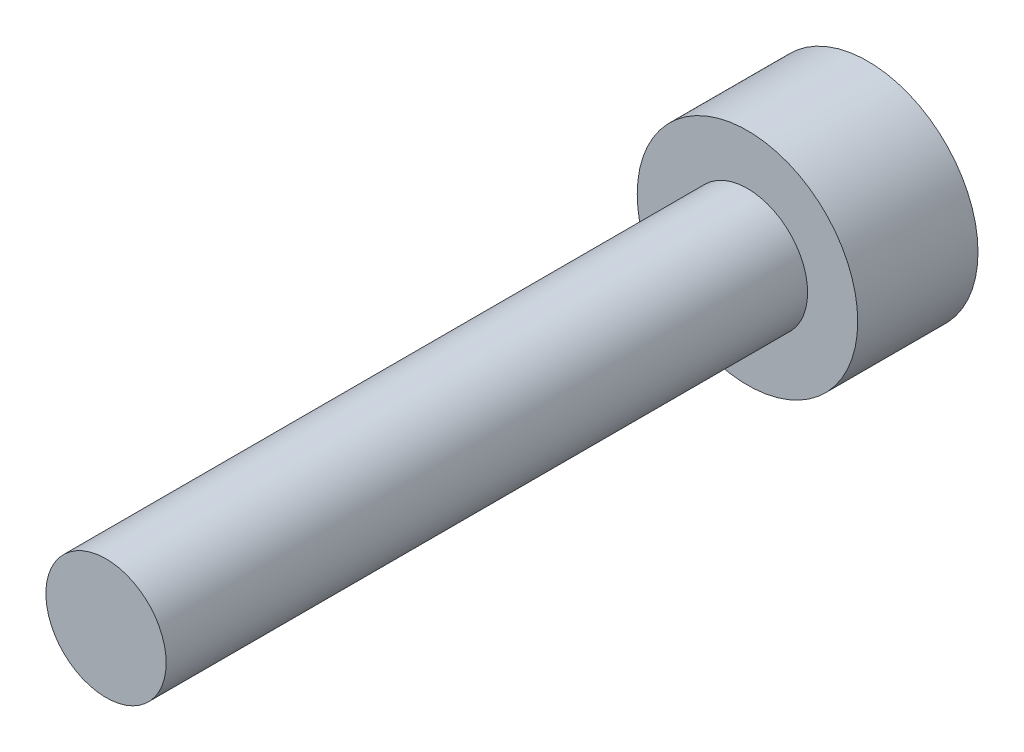
SolidWorks part; units mm, degrees
ref_plane "Plano frontal" through (0, 0, 0) normal (0, 0, 1) x (1, 0, 0)
ref_plane "Plano superior" through (0, 0, 0) normal (0, 1, 0) x (1, 0, 0)
ref_plane "Plano direito" through (0, 0, 0) normal (1, 0, 0) x (0, 0, -1)
sketch "Esboço1" plane through (0, 0, 0) normal (0, 1, 0) x (1, 0, 0)
  line L0 (0, 0) -> (2.75, 0)
  line L1 (2.75, 0) -> (2.75, -3)
  line L2 (2.75, -3) -> (1.5, -3)
  line L3 (0, -3) -> (0, 0)
  line L5 (1.5, -3) -> (1.5, -19)
  line L6 (1.5, -19) -> (0, -19)
  line L7 (0, -19) -> (0, -3)
revolve "Revolução1" add sketch "Esboço1" angle 360 about L3
sketch "Esboço2" plane through (0, 0, 0) normal (0, 0, -1) x (-1, 0, 0)
  line L1 (1.7321, 0) -> (0.866, 1.5)
  line L2 (0.866, 1.5) -> (-0.866, 1.5)
  line L3 (-0.866, 1.5) -> (-1.7321, 0)
  line L4 (-1.7321, 0) -> (-0.866, -1.5)
  line L5 (-0.866, -1.5) -> (0.866, -1.5)
  line L6 (0.866, -1.5) -> (1.7321, 0)
  circle A0 centre (0, 0) radius 1.5 construction
extrude "Corte-extrusão1" cut sketch "Esboço2" against normal blind 1.5
